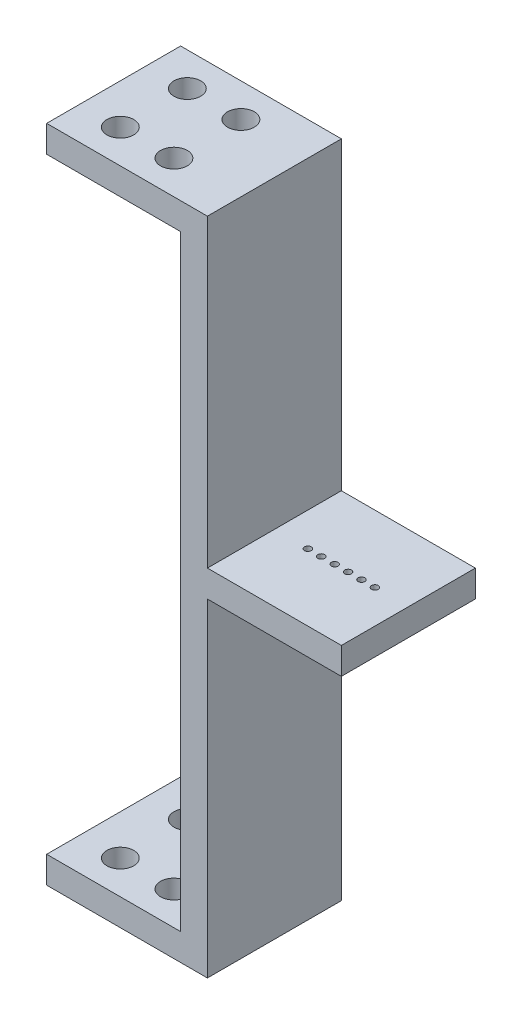
SolidWorks part; units mm, degrees
ref_plane "Front Plane" through (0, 0, 0) normal (0, 0, 1) x (1, 0, 0)
ref_plane "Top Plane" through (0, 0, 0) normal (0, 1, 0) x (1, 0, 0)
ref_plane "Right Plane" through (0, 0, 0) normal (1, 0, 0) x (0, 0, -1)
sketch "Sketch1" plane through (0, 0, 0) normal (0, 0, 1) x (1, 0, 0)
  line L0 (-24, 49.25) -> (0, 49.25)
  line L1 (0, 49.25) -> (0, 3.75)
  line L2 (0, -49.25) -> (-24, -49.25)
  line L3 (-24, 45.25) -> (-4, 45.25)
  line L4 (-4, 45.25) -> (-4, -45.25)
  line L5 (-4, -45.25) -> (-24, -45.25)
  line L6 (-24, 49.25) -> (-24, 45.25)
  line L7 (-24, -49.25) -> (-24, -45.25)
  line L8 (0, 3.75) -> (20, 3.75)
  line L9 (20, 3.75) -> (20, -0.25)
  line L10 (20, -0.25) -> (0, -0.25)
  line L11 (0, -0.25) -> (0, -49.25)
  line L12 (0, 49.25) -> (0, -49.25) construction
  point P9 (-4, 0)
  dimension "D2" = 98.5
  dimension "D3" = 20
  dimension "D4" = 4
  dimension "D5" = 20
  dimension "D6" = 45
  dimension "D1" = 4
extrude "Boss-Extrude1" add sketch "Sketch1" along normal blind 20
sketch "Sketch2" plane through (0, 49.25, 0) normal (0, 1, 0) x (1, 0, 0)
  line L1 (-18, -5) -> (-10, -5)
  line L2 (-18, -5) -> (-18, -15)
  line L3 (-18, -15) -> (-10, -15)
  line L4 (-10, -5) -> (-10, -15)
  line L5 (-18, -5) -> (-10, -15) construction
  line L6 (-18, -15) -> (-10, -5) construction
  line L7 (-24, 0) -> (-4, 0) construction
  line L8 (-24, -20) -> (-24, 0) construction
  circle A0 centre (-18, -5) radius 2
  circle A1 centre (-10, -5) radius 2
  circle A2 centre (-10, -15) radius 2
  circle A3 centre (-18, -15) radius 2
  point P0 (-14, -10)
  point P5 (-14, -5)
  point P11 (-14, 0)
  point P12 (-18, -10)
  point P15 (-24, -10)
  dimension "D3" = 4
  dimension "D1" = 8
  dimension "D2" = 10
extrude "Cut-Extrude1" cut sketch "Sketch2" against normal through all contours A0 | A1 | A2 | A3
sketch "Sketch4" plane through (0, 3.75, 0) normal (0, 1, 0) x (1, 0, 0)
  line L0 (20, -20) -> (20, 0) construction
  circle A0 centre (15, -10) radius 0.5
  circle A1 centre (13, -10) radius 0.5
  circle A2 centre (11, -10) radius 0.5
  circle A3 centre (9, -10) radius 0.5
  circle A4 centre (7, -10) radius 0.5
  circle A5 centre (5, -10) radius 0.5
  point P5 (20, -10)
  dimension "D1" = 1
  dimension "D2" = 5
  dimension "D4" = 2
  dimension "D3" = 6
extrude "Cut-Extrude2" cut sketch "Sketch4" against normal blind 20
